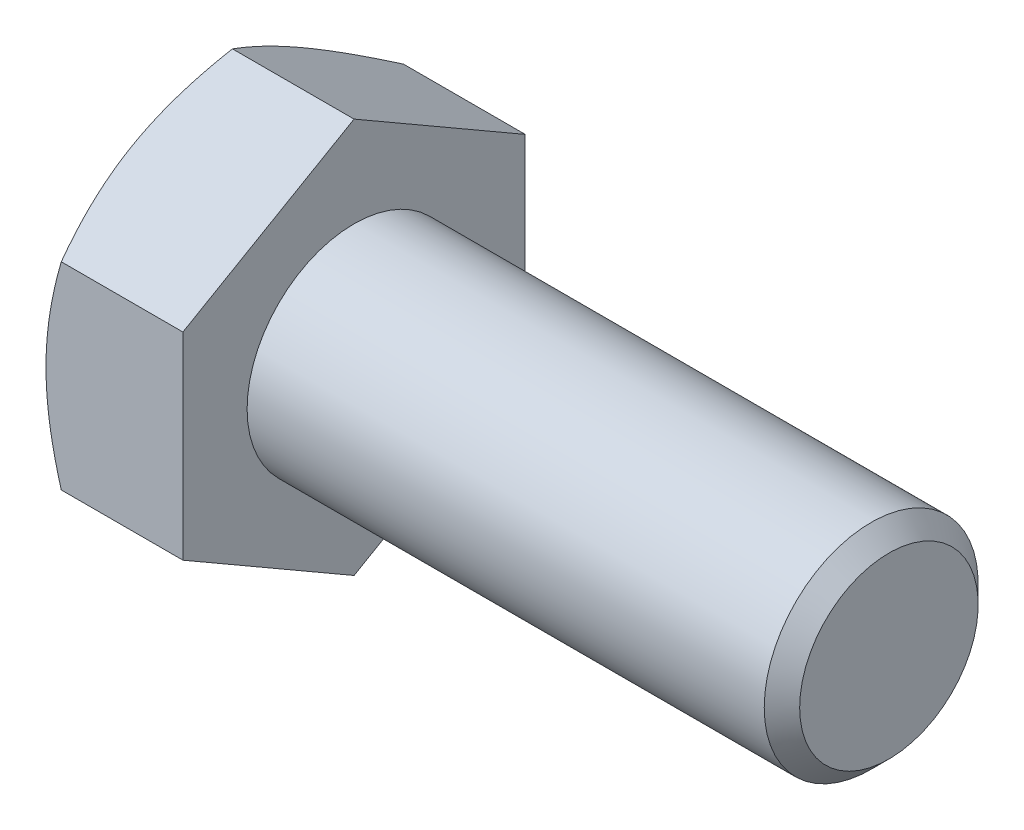
SolidWorks part; units mm, degrees
extrude "BaseHead" add sketch "Sketch1" along normal blind 6.4
sketch "Sketch1" plane through (0, 0, 0) normal (1, 0, 0) x (0, 0, -1)
  line L0 (8, 4.6188) -> (8, -4.6188)
  line L1 (-8, 4.6188) -> (-8, -4.6188)
  line L2 (8, -4.6188) -> (0, -9.2376)
  line L3 (0, -9.2376) -> (-8, -4.6188)
  line L4 (8, 4.6188) -> (0, 9.2376)
  line L5 (0, 9.2376) -> (-8, 4.6188)
  dimension "Width_flats" = 16
  dimension "D2" = 120
  dimension "D3" = 8
  dimension "D4" = 8
  dimension "D5" = 8
ref_plane "Plane1" through (0, 0, 0) normal (0, 0, 1) x (1, 0, 0)
ref_plane "Plane2" through (0, 0, 0) normal (0, 1, 0) x (1, 0, 0)
ref_plane "Plane3" through (0, 0, 0) normal (1, 0, 0) x (0, 0, -1)
sketch "BodySke" plane through (0, 0, 0) normal (0, 0, 1) x (1, 0, 0)
  line L1 (0, 0) -> (31.4, 0)
  line L2 (0, 0) -> (0, 5)
  line L4 (31.4, 0) -> (31.4, 4.172)
  line L5 (6.4, 9.2376) -> (6.4, 4.6188) construction
  line L6 (31.4, 4.172) -> (30.572, 5)
  line L7 (0, 0) -> (110.49, 0) construction
  line L8 (31.4, -4.172) -> (30.572, -5) construction
  line L9 (0, 4.6188) -> (0, -4.6188) construction
  line L10 (7.9, 15.24) -> (7.9, -1.27) construction
  line L11 (5.4, 15.24) -> (5.4, -1.27) construction
  line L12 (6.4, 4.6188) -> (6.4, -4.6188) construction
  line L15 (0, 5) -> (30.572, 5)
  dimension "Body_ch_ang" = 45
  dimension "Minor_dia" = 8.344
  dimension "Diameter" = 10
revolve "BaseBody" add sketch "BodySke" angle 360 about L7
cosmetic thread "ThreadCosmetic" [suppressed] parameters "Thread_length"=23.5, "Thread_minor"=8.344
fillet "HeadFillet" [suppressed] radius 0.4
sketch "Sketch3" plane through (0, 0, 0) normal (0, 0, 1) x (1, 0, 0)
  line L0 (0, 8) -> (3.6013, 14.2376)
  line L1 (0, 9.2376) -> (0, 4.6188) construction
  line L2 (3.6013, 14.2376) -> (3.6013, 19.2376)
  line L3 (3.6013, 19.2376) -> (-10, 19.2376)
  line L4 (-10, 19.2376) -> (-10, 8)
  line L5 (-10, 8) -> (0, 8)
  line L6 (0, 0) -> (99.06, 0) construction
  line L7 (6.4, 9.2376) -> (0, 9.2376) construction
  dimension "D1" = 8
  dimension "D2" = 5
  dimension "D3" = 10
  dimension "D4" = 5
  dimension "Head_ch_ang" = 30
revolve "HeadChamfer" cut sketch "Sketch3" angle 360 about L6
sketch "ThdSchSke" plane through (0, 0, 0) normal (0, 0, 1) x (1, 0, 0)
  line L0 (7.9, -4.172) -> (7.3202, -5)
  line L1 (7.9, -4.172) -> (8.4798, -5)
  line L2 (8.4798, -5) -> (8.4798, -6.25)
  line L3 (-3.175, 0) -> (5.1513, 0) construction
  line L5 (8.4798, -6.25) -> (7.3202, -6.25)
  line L6 (7.3202, -6.25) -> (7.3202, -5)
  dimension "Thread_minor" = 8.344
  dimension "Diameter" = 10
  dimension "Start" = 7.9
revolve "ThreadSchematic" [suppressed] cut sketch "ThdSchSke" angle 360 about L3
pattern_linear "ThdSchPat" [suppressed]
equation "\"D3@Sketch1\" = \"Width_flats@Sketch1\" / 2"
equation "\"D4@Sketch1\" = \"D3@Sketch1\""
equation "\"D5@Sketch1\" = \"D4@Sketch1\""
equation "\"Thread_minor@ThreadCosmetic\" = \"Minor_dia@BodySke\""
equation "\"D1@Sketch3\" = \"Width_flats@Sketch1\" / 2"
equation "\"Thread_length@ThreadCosmetic\" = ((sgn( (\"Length@BodySke\" - \"Advance@BodySke\" ) - \"Thread_nom@BodySke\" )-1)*( (\"Length@BodySke\" - \"Advance@BodySke\" ) - \"Thread_nom@BodySke\" ))/-2+ \"Thread_nom@BodySke\""
equation "\"Thread_minor@ThdSchSke\" = \"Minor_dia@BodySke\""
equation "\"Diameter@ThdSchSke\" = \"Diameter@BodySke\""
equation "\"Overcut@ThdSchSke\" = \"Diameter@BodySke\" * 1.25"
equation "\"Start@ThdSchSke\" = \"Head_ht@BaseHead\" + \"Length@BodySke\" - \"Thread_length@ThreadCosmetic\"  '---Non-countersunk---"
equation "\"Num_threads@ThdSchPat\" = int( \"Thread_length@ThreadCosmetic\" / \"Advance@BodySke\" + 0.999 )  + 1"
equation "\"Advance@ThdSchPat\" = \"Thread_length@ThreadCosmetic\" /  (\"Num_threads@ThdSchPat\" - 1) 'relax it"
equation "\"Num_threads@ThdSchPat\" = \"Num_threads@ThdSchPat\" - sgn( \"Num_threads@ThdSchPat\" - 1) '---chamfered tips only---"
